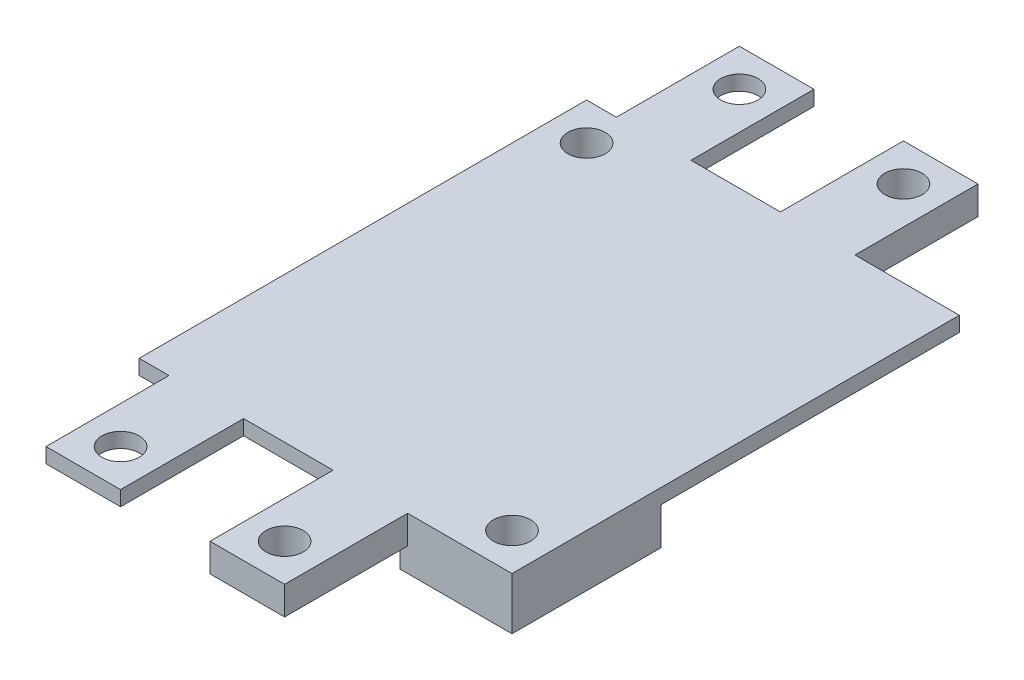
SolidWorks part; units mm, degrees
ref_plane "Front Plane" through (0, 0, 0) normal (0, 0, 1) x (1, 0, 0)
ref_plane "Top Plane" through (0, 0, 0) normal (0, 1, 0) x (1, 0, 0)
ref_plane "Right Plane" through (0, 0, 0) normal (1, 0, 0) x (0, 0, -1)
sketch "Sketch1" plane through (0, 0, 0) normal (0, 1, 0) x (1, 0, 0)
  line L1 (0, 0) -> (50, 0)
  line L2 (0, 0) -> (0, 60)
  line L3 (0, 60) -> (50, 60)
  line L4 (50, 0) -> (50, 60)
  dimension "D1" = 50
  dimension "D2" = 60
extrude "Boss-Extrude1" add sketch "Sketch1" along normal blind 2
sketch "Sketch2" plane through (0, 0, 0) normal (0, -1, 0) x (1, 0, 0)
  line L1 (50, 0) -> (35, 0)
  line L2 (50, 0) -> (50, -20)
  line L3 (50, -20) -> (35, -20)
  line L4 (35, 0) -> (35, -20)
  line L5 (0, -60) -> (15, -60)
  line L6 (0, -60) -> (0, -46)
  line L7 (0, -46) -> (15, -46)
  line L8 (15, -60) -> (15, -46)
  dimension "D1" = 15
  dimension "D2" = 20
  dimension "D3" = 15
  dimension "D4" = 14
extrude "Boss-Extrude2" add sketch "Sketch2" along normal blind 5
sketch "Sketch3" plane through (0, 2, 0) normal (0, 1, 0) x (1, 0, 0)
  line L0 (50, 60) -> (0, 60) construction
  line L1 (0, 60) -> (0, 0) construction
  line L2 (50, 0) -> (50, 60) construction
  line L3 (0, 0) -> (50, 0) construction
  circle A0 centre (45, 5) radius 2.5
  circle A1 centre (5, 55) radius 2.5
  dimension "D3" = 5
  dimension "D1" = 5
  dimension "D2" = 5
  dimension "D4" = 5
  dimension "D5" = 5
extrude "Cut-Extrude1" cut sketch "Sketch3" against normal up to surface (7 mm away) up to face at (7.5, -5, -53)
sketch "Sketch4" plane through (0, 2, 0) normal (0, 1, 0) x (1, 0, 0)
  line L0 (50, 60) -> (0, 60) construction
  line L1 (4, 60) -> (14, 60)
  line L2 (4, 60) -> (4, 76.5)
  line L3 (4, 76.5) -> (14, 76.5)
  line L4 (14, 60) -> (14, 76.5)
  line L5 (0, 0) -> (50, 0) construction
  line L6 (4, 0) -> (14, 0)
  line L7 (4, 0) -> (4, -16.5)
  line L8 (4, -16.5) -> (14, -16.5)
  line L9 (14, 0) -> (14, -16.5)
  line L10 (0, 60) -> (0, 0) construction
  circle A0 centre (9, -11.5) radius 2.5
  circle A1 centre (9, 71.5) radius 2.5
  point P16 (0, 0)
  point P19 (9, -16.5)
  dimension "D1" = 5
  dimension "D2" = 9
  dimension "D3" = 10
  dimension "D4" = 5
  dimension "D5" = 5
  dimension "D6" = 83
extrude "Boss-Extrude3" add sketch "Sketch4" against normal up to surface (2 mm away) up to face at (25, 0, -31.5)
sketch "Sketch5" plane through (0, 2, 0) normal (0, 1, 0) x (1, 0, 0)
  line L0 (50, 60) -> (14, 60) construction
  line L1 (26, 60) -> (36, 60)
  line L2 (26, 60) -> (26, 76.5)
  line L3 (26, 76.5) -> (36, 76.5)
  line L4 (36, 60) -> (36, 76.5)
  line L5 (14, 0) -> (50, 0) construction
  line L6 (26, 0) -> (36, 0)
  line L7 (26, 0) -> (26, -16.5)
  line L8 (26, -16.5) -> (36, -16.5)
  line L9 (36, 0) -> (36, -16.5)
  line L10 (14, 76.5) -> (4, 76.5) construction
  line L11 (4, -16.5) -> (14, -16.5) construction
  circle A0 centre (31, 71.5) radius 2.5
  circle A1 centre (31, -11.5) radius 2.5
  point P16 (0, 0)
  point P17 (9, -11.5)
  point P20 (9, 71.5)
  point P21 (0, 0)
  point P24 (31, 76.5)
  dimension "D1" = 5
  dimension "D2" = 22
extrude "Boss-Extrude5" add sketch "Sketch5" against normal offset from surface (3.8 mm away) 1.8 up to face at (19.6667, 0, -18.25) offset beyond the face yes
